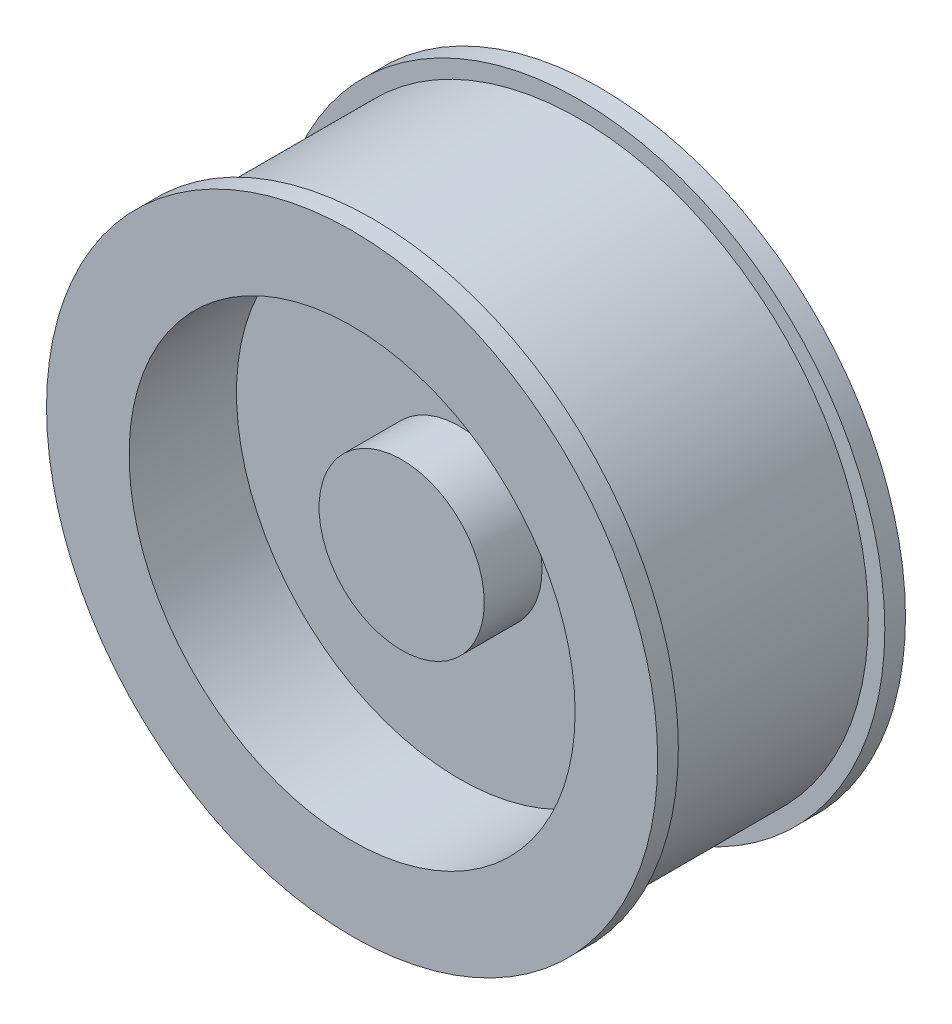
SolidWorks part; units mm, degrees
ref_plane "Alzado" through (0, 0, 0) normal (0, 0, 1) x (1, 0, 0)
ref_plane "Planta" through (0, 0, 0) normal (0, 1, 0) x (1, 0, 0)
ref_plane "Vista lateral" through (0, 0, 0) normal (1, 0, 0) x (0, 0, -1)
sketch "Croquis2" plane through (0, 0, 0) normal (1, 0, 0) x (0, 0, -1)
  line L0 (0, -1172) -> (0, -86) construction
  line L3 (-30, -90) -> (-25, -90)
  line L4 (30, -70) -> (30, -90)
  line L5 (25, -90) -> (30, -90)
  line L7 (-25, -90) -> (-25, -86)
  line L8 (-25, -86) -> (25, -86)
  line L9 (25, -90) -> (25, -86)
  line L10 (14.6133, -16) -> (50014.6133, -16) construction
  line L11 (-4, -86) -> (4, -86)
  line L12 (-4, -70) -> (-4, -36)
  line L14 (4, -70) -> (4, -36)
  line L15 (18, -36) -> (4, -36)
  line L16 (18, -36) -> (18, -16)
  line L17 (18, -16) -> (-18, -16)
  line L18 (-18, -36) -> (-18, -16)
  line L19 (25, -86) -> (-25, -86)
  line L20 (30, -86) -> (30, -70)
  line L21 (30, -70) -> (4, -70)
  line L22 (-30, -86) -> (-30, -70)
  line L23 (-4, -70) -> (-30, -70)
  line L24 (-4, -36) -> (-18, -36)
  line L25 (-30, -70) -> (-30, -90)
  line L26 (0, -16) -> (0, 0) construction
  point P0 (30, -80)
  point P13 (0, -86)
  dimension "D1" = 60
  dimension "D2" = 50
  dimension "D3" = 26
  dimension "D4" = 20
  dimension "D5" = 34
  dimension "D6" = 20
  dimension "D7" = 16
  dimension "D8" = 36
revolve "Revolución2" add sketch "Croquis2" angle 360 about L10
